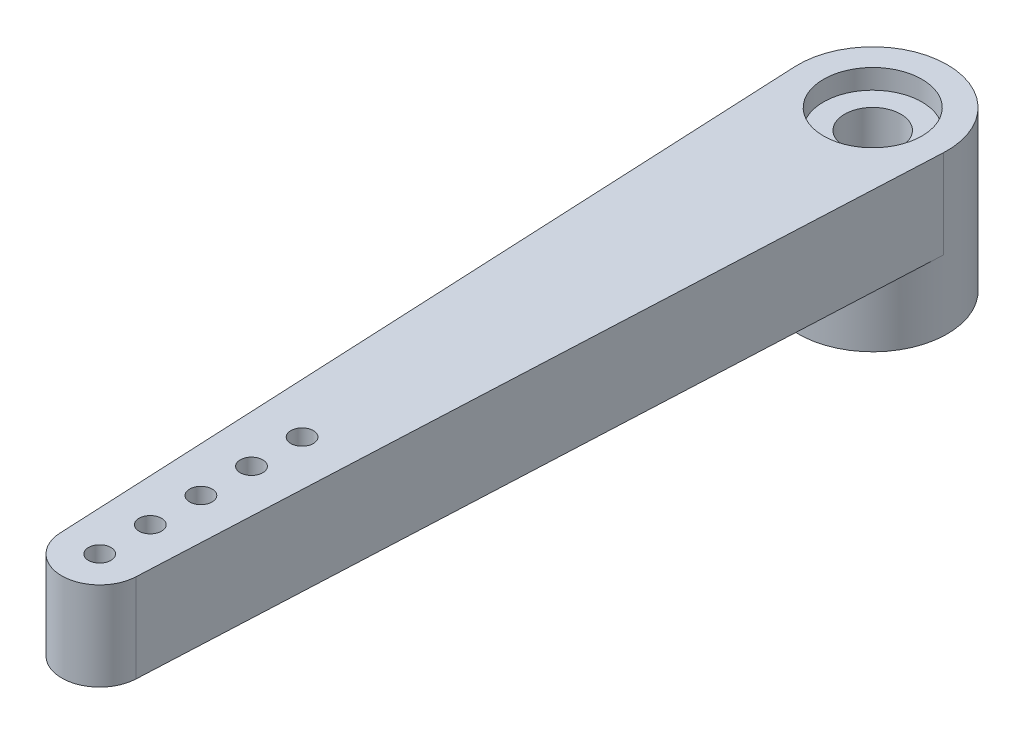
SolidWorks part; units mm, degrees
ref_plane "Front Plane" through (0, 0, 0) normal (0, 0, 1) x (1, 0, 0)
ref_plane "Top Plane" through (0, 0, 0) normal (0, 1, 0) x (1, 0, 0)
ref_plane "Right Plane" through (0, 0, 0) normal (1, 0, 0) x (0, 0, -1)
sketch "Sketch1" plane through (0, 0, 0) normal (0, 1, 0) x (1, 0, 0)
  line L0 (0, 0) -> (0, -34.92) construction
  line L1 (-1.7126, -35.0011) -> (-3.3617, -0.1591)
  line L2 (1.7126, -35.0011) -> (3.3617, -0.1591)
  arc A0 (3.3617, -0.1591) -> (-3.3617, -0.1591) centre (0, 0) ccw
  arc A1 (-1.7126, -35.0011) -> (1.7126, -35.0011) centre (0, -34.92) ccw
  dimension "D1" = 6.731
  dimension "D2" = 3.429
  dimension "D3" = 40
extrude "Boss-Extrude1" add sketch "Sketch1" along normal blind 4
sketch "Sketch2" plane through (0, 0, 0) normal (0, -1, 0) x (1, 0, 0)
  circle A0 centre (0, 0) radius 3.3655
extrude "Boss-Extrude2" add sketch "Sketch2" along normal blind 3.175
sketch "Sketch3" plane through (0, -3.175, 0) normal (0, -1, 0) x (-1, 0, 0)
  line L0 (0.3447, 2.4524) -> (0.1605, 2.2167)
  line L1 (0, 2.4765) -> (-0.1496, 2.2175)
  line L2 (0.4567, 2.1751) -> (0.3447, 2.4524)
  line L3 (0.1496, 2.2175) -> (0, 2.4765)
  line L4 (0.6826, 2.3806) -> (0.4675, 2.1728)
  line L5 (0.755, 2.0903) -> (0.6826, 2.3806)
  line L6 (1.0073, 2.2624) -> (0.7653, 2.0866)
  line L7 (1.0385, 1.9649) -> (1.0073, 2.2624)
  line L8 (1.3123, 2.1002) -> (1.0482, 1.9598)
  line L9 (1.3019, 1.8013) -> (1.3123, 2.1002)
  line L10 (1.5919, 1.8971) -> (1.3108, 1.7948)
  line L11 (1.5399, 1.6025) -> (1.5919, 1.8971)
  line L12 (1.8404, 1.6571) -> (1.5478, 1.5949)
  line L13 (1.748, 1.3726) -> (1.8404, 1.6571)
  line L14 (2.0531, 1.3848) -> (1.7547, 1.364)
  line L15 (1.922, 1.116) -> (2.0531, 1.3848)
  line L16 (2.2259, 1.0856) -> (1.9275, 1.1065)
  line L17 (2.0586, 0.8377) -> (2.2259, 1.0856)
  line L18 (2.3553, 0.7653) -> (2.0627, 0.8275)
  line L19 (2.1551, 0.543) -> (2.3553, 0.7653)
  line L20 (2.4389, 0.43) -> (2.1578, 0.5323)
  line L21 (2.2097, 0.2378) -> (2.4389, 0.43)
  line L22 (2.475, 0.0864) -> (2.2109, 0.2269)
  line L23 (2.2213, -0.0721) -> (2.475, 0.0864)
  line L24 (2.4629, -0.2589) -> (2.2209, -0.0831)
  line L25 (2.1897, -0.3805) -> (2.4629, -0.2589)
  line L26 (2.4029, -0.5991) -> (2.1878, -0.3913)
  line L27 (2.1154, -0.6816) -> (2.4029, -0.5991)
  line L28 (2.2962, -0.9277) -> (2.112, -0.692)
  line L29 (2, -0.9693) -> (2.2962, -0.9277)
  line L30 (2.1447, -1.2383) -> (1.9952, -0.9792)
  line L31 (1.8456, -1.2382) -> (2.1447, -1.2383)
  line L32 (1.9515, -1.5247) -> (1.8395, -1.2474)
  line L33 (1.6553, -1.4831) -> (1.9515, -1.5247)
  line L34 (1.7203, -1.7814) -> (1.648, -1.4912)
  line L35 (1.4328, -1.699) -> (1.7203, -1.7814)
  line L36 (1.4557, -2.0035) -> (1.4244, -1.7061)
  line L37 (1.1824, -1.8819) -> (1.4557, -2.0035)
  line L38 (1.1626, -2.1866) -> (1.1731, -1.8877)
  line L39 (0.909, -2.0281) -> (1.1626, -2.1866)
  line L40 (0.847, -2.3271) -> (0.899, -2.0326)
  line L41 (0.6179, -2.1349) -> (0.847, -2.3271)
  line L42 (0.5149, -2.4224) -> (0.6073, -2.1379)
  line L43 (0.3147, -2.2001) -> (0.5149, -2.4224)
  line L44 (0.1728, -2.4705) -> (0.3039, -2.2016)
  line L45 (-0.22, 2.0955) -> (0, 2.0955) [skipped]
  line L46 (0.0055, -2.2225) -> (0.1728, -2.4705)
  line L47 (-0.1728, -2.4705) -> (-0.0055, -2.2225)
  line L48 (-0.3039, -2.2016) -> (-0.1728, -2.4705)
  line L49 (-0.5149, -2.4224) -> (-0.3147, -2.2001)
  line L50 (-0.6073, -2.1379) -> (-0.5149, -2.4224)
  line L51 (-0.847, -2.3271) -> (-0.6179, -2.1349)
  line L52 (-0.899, -2.0326) -> (-0.847, -2.3271)
  line L53 (-1.1626, -2.1866) -> (-0.909, -2.0281)
  line L54 (-1.1731, -1.8877) -> (-1.1626, -2.1866)
  line L55 (-1.4557, -2.0035) -> (-1.1824, -1.8819)
  line L56 (-1.4244, -1.7061) -> (-1.4557, -2.0035)
  line L57 (-1.7203, -1.7814) -> (-1.4328, -1.699)
  line L58 (-1.648, -1.4912) -> (-1.7203, -1.7814)
  line L59 (-1.9515, -1.5247) -> (-1.6553, -1.4831)
  line L60 (-1.8395, -1.2474) -> (-1.9515, -1.5247)
  line L61 (-2.1447, -1.2382) -> (-1.8456, -1.2383)
  line L62 (-1.9952, -0.9792) -> (-2.1447, -1.2382)
  line L63 (-2.2962, -0.9277) -> (-2, -0.9693)
  line L64 (-2.112, -0.692) -> (-2.2962, -0.9277)
  line L65 (-2.4029, -0.5991) -> (-2.1154, -0.6816)
  line L66 (-2.1878, -0.3913) -> (-2.4029, -0.5991)
  line L67 (-2.4629, -0.2589) -> (-2.1897, -0.3805)
  line L68 (-2.2209, -0.0831) -> (-2.4629, -0.2589)
  line L69 (-2.475, 0.0864) -> (-2.2213, -0.0721)
  line L70 (-2.2109, 0.2269) -> (-2.475, 0.0864)
  line L71 (-2.4389, 0.43) -> (-2.2097, 0.2378)
  line L72 (-2.1578, 0.5323) -> (-2.4389, 0.43)
  line L73 (-2.3553, 0.7653) -> (-2.1551, 0.543)
  line L74 (-2.0627, 0.8275) -> (-2.3553, 0.7653)
  line L75 (-2.2259, 1.0856) -> (-2.0586, 0.8377)
  line L76 (-1.9275, 1.1065) -> (-2.2259, 1.0856)
  line L77 (-2.0531, 1.3848) -> (-1.922, 1.116)
  line L78 (-1.7547, 1.364) -> (-2.0531, 1.3848)
  line L79 (-1.8404, 1.6571) -> (-1.748, 1.3726)
  line L80 (-1.5478, 1.5949) -> (-1.8404, 1.6571)
  line L81 (-1.5919, 1.8971) -> (-1.5399, 1.6025)
  line L82 (-1.3108, 1.7948) -> (-1.5919, 1.8971)
  line L83 (-1.3123, 2.1002) -> (-1.3019, 1.8013)
  line L84 (-1.0482, 1.9598) -> (-1.3123, 2.1002)
  line L85 (-1.0073, 2.2624) -> (-1.0385, 1.9649)
  line L86 (-0.7653, 2.0866) -> (-1.0073, 2.2624)
  line L87 (-0.6826, 2.3806) -> (-0.755, 2.0903)
  line L88 (-0.4675, 2.1728) -> (-0.6826, 2.3806)
  line L89 (-0.3447, 2.4524) -> (-0.4567, 2.1751)
  line L90 (-0.1605, 2.2167) -> (-0.3447, 2.4524)
  arc A0 (-0.1496, 2.2175) -> (-0.1605, 2.2167) centre (0, 0) ccw
  circle A1 centre (0, 2.2225) radius 0.127 construction
  arc A2 (0.1605, 2.2167) -> (0.1496, 2.2175) centre (0, 0) ccw
  arc A3 (0.4675, 2.1728) -> (0.4567, 2.1751) centre (0, 0) ccw
  arc A4 (0.7653, 2.0866) -> (0.755, 2.0903) centre (0, 0) ccw
  arc A5 (1.0482, 1.9598) -> (1.0385, 1.9649) centre (0, 0) ccw
  arc A6 (1.3108, 1.7948) -> (1.3019, 1.8013) centre (0, 0) ccw
  arc A7 (1.5478, 1.5949) -> (1.5399, 1.6025) centre (0, 0) ccw
  arc A8 (1.7547, 1.364) -> (1.748, 1.3726) centre (0, 0) ccw
  arc A9 (1.9275, 1.1065) -> (1.922, 1.116) centre (0, 0) ccw
  arc A10 (-0.4567, 2.1751) -> (-0.4675, 2.1728) centre (0, 0) ccw
  arc A11 (-0.755, 2.0903) -> (-0.7653, 2.0866) centre (0, 0) ccw
  arc A12 (-1.0385, 1.9649) -> (-1.0482, 1.9598) centre (0, 0) ccw
  arc A13 (-1.3019, 1.8013) -> (-1.3108, 1.7948) centre (0, 0) ccw
  arc A14 (-1.5399, 1.6025) -> (-1.5478, 1.5949) centre (0, 0) ccw
  arc A15 (-1.748, 1.3726) -> (-1.7547, 1.364) centre (0, 0) ccw
  arc A16 (-1.922, 1.116) -> (-1.9275, 1.1065) centre (0, 0) ccw
  arc A17 (-2.0586, 0.8377) -> (-2.0627, 0.8275) centre (0, 0) ccw
  arc A18 (-2.1551, 0.543) -> (-2.1578, 0.5323) centre (0, 0) ccw
  arc A19 (-2.2097, 0.2378) -> (-2.2109, 0.2269) centre (0, 0) ccw
  arc A20 (-2.2213, -0.0721) -> (-2.2209, -0.0831) centre (0, 0) ccw
  arc A21 (2.0627, 0.8275) -> (2.0586, 0.8377) centre (0, 0) ccw
  arc A22 (2.1578, 0.5323) -> (2.1551, 0.543) centre (0, 0) ccw
  arc A23 (2.2109, 0.2269) -> (2.2097, 0.2378) centre (0, 0) ccw
  arc A24 (2.2209, -0.0831) -> (2.2213, -0.0721) centre (0, 0) ccw
  arc A25 (2.1878, -0.3913) -> (2.1897, -0.3805) centre (0, 0) ccw
  arc A26 (2.112, -0.692) -> (2.1154, -0.6816) centre (0, 0) ccw
  arc A27 (1.9952, -0.9792) -> (2, -0.9693) centre (0, 0) ccw
  arc A28 (1.8395, -1.2474) -> (1.8456, -1.2382) centre (0, 0) ccw
  arc A29 (1.648, -1.4912) -> (1.6553, -1.4831) centre (0, 0) ccw
  arc A30 (1.4244, -1.7061) -> (1.4328, -1.699) centre (0, 0) ccw
  arc A31 (1.1731, -1.8877) -> (1.1824, -1.8819) centre (0, 0) ccw
  arc A32 (0.899, -2.0326) -> (0.909, -2.0281) centre (0, 0) ccw
  arc A33 (0.6073, -2.1379) -> (0.6179, -2.1349) centre (0, 0) ccw
  arc A34 (0.3039, -2.2016) -> (0.3147, -2.2001) centre (0, 0) ccw
  arc A35 (-0.0055, -2.2225) -> (0.0055, -2.2225) centre (0, 0) ccw
  arc A36 (-0.3147, -2.2001) -> (-0.3039, -2.2016) centre (0, 0) ccw
  arc A37 (-0.6179, -2.1349) -> (-0.6073, -2.1379) centre (0, 0) ccw
  arc A38 (-0.909, -2.0281) -> (-0.899, -2.0326) centre (0, 0) ccw
  arc A39 (-1.1824, -1.8819) -> (-1.1731, -1.8877) centre (0, 0) ccw
  arc A40 (-1.4328, -1.699) -> (-1.4244, -1.7061) centre (0, 0) ccw
  arc A41 (-1.6553, -1.4831) -> (-1.648, -1.4912) centre (0, 0) ccw
  arc A42 (-1.8456, -1.2383) -> (-1.8395, -1.2474) centre (0, 0) ccw
  arc A43 (-2, -0.9693) -> (-1.9952, -0.9792) centre (0, 0) ccw
  arc A44 (-2.1154, -0.6816) -> (-2.112, -0.692) centre (0, 0) ccw
  arc A45 (-2.1897, -0.3805) -> (-2.1878, -0.3913) centre (0, 0) ccw
  point P145 (0, 0)
  dimension "D1" = 4.445
  dimension "D2" = 0.254
  dimension "D3" = 45
extrude "Cut-Extrude1" cut sketch "Sketch3" against normal blind 2.286
sketch "Sketch4" plane through (0, 4, 0) normal (0, 1, 0) x (1, 0, 0)
  circle A0 centre (0, 0) radius 2.2225
  dimension "D1" = 4.445
extrude "Cut-Extrude2" cut sketch "Sketch4" against normal blind 0.889
sketch "Sketch5" plane through (0, 3.111, 0) normal (0, 1, 0) x (1, 0, 0)
  circle A0 centre (0, 0) radius 1.27
  dimension "D1" = 2.54
extrude "Cut-Extrude3" cut sketch "Sketch5" against normal up to next
sketch "Sketch6" plane through (0, 4, 0) normal (0, 1, 0) x (1, 0, 0)
  line L0 (0, 0) -> (0, -34.92) construction
  circle A0 centre (0, -34.92) radius 0.508
  circle A1 centre (0, -32.634) radius 0.508
  circle A2 centre (0, -30.348) radius 0.508
  circle A3 centre (0, -28.062) radius 0.508
  circle A4 centre (0, -25.776) radius 0.508
  dimension "D1" = 1.016
  dimension "D2" = 1.016
  dimension "D3" = 1.27
  dimension "D4" = 1.27
  dimension "D5" = 1.27
  dimension "D6" = 1.27
extrude "Cut-Extrude4" cut sketch "Sketch6" against normal up to next
